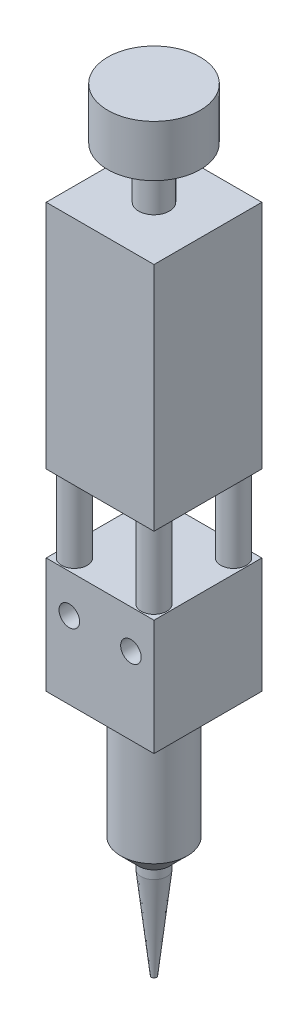
SolidWorks part; units mm, degrees
material "3.1355 (EN-AW 2024)"
ref_plane "Спереди" through (0, 0, 0) normal (0, 0, 1) x (1, 0, 0)
ref_plane "Сверху" through (0, 0, 0) normal (0, 1, 0) x (1, 0, 0)
ref_plane "Справа" through (0, 0, 0) normal (1, 0, 0) x (0, 0, -1)
sketch "Эскиз1" plane through (0, 0, 0) normal (0, 1, 0) x (1, 0, 0)
  line L1 (-10.5, 10.5) -> (10.5, 10.5)
  line L2 (-10.5, 10.5) -> (-10.5, -10.5)
  line L3 (-10.5, -10.5) -> (10.5, -10.5)
  line L4 (10.5, 10.5) -> (10.5, -10.5)
  line L5 (-10.5, 10.5) -> (10.5, -10.5) construction
  line L6 (-10.5, -10.5) -> (10.5, 10.5) construction
  point P0 (0, 0)
  dimension "D1" = 21
extrude "База" add sketch "Эскиз1" along normal blind 22.5
sketch "Эскиз2" plane through (0, 0, 0) normal (0, 0, 1) x (1, 0, 0)
  line L0 (0, 0) -> (6.5, 0)
  line L1 (-10.5, 0) -> (10.5, 0) construction
  line L2 (6.5, 0) -> (6.5, -24.5)
  line L3 (6.5, -24.5) -> (3, -28)
  line L4 (3, -28) -> (0, -28)
  line L5 (0, -28) -> (0, 0)
  dimension "D1" = 28
  dimension "D2" = 3
  dimension "D3" = 6.5
  dimension "D4" = 45
revolve "Повернуть1" add sketch "Эскиз2" angle 360 about L5
hole_wizard "Диаметр отверстия Ø4.0 (4)1" positions "Эскиз3" profile "Эскиз4" hole size "Ø4.0" standard "DIN" end condition through all
sketch "Эскиз3" plane through (0, 0, 10.5) normal (0, 0, 1) x (1, 0, 0)
  line L0 (6, 15) -> (0, 15) construction
  line L1 (0, 15) -> (-6, 15) construction
  point P0 (-6, 15)
  point P2 (6, 15)
  dimension "D1" = 12
  dimension "D2" = 15
sketch "Эскиз4" plane through (-6, 15, 10.5) normal (1, 0, 0) x (0, -1, 0)
  line L0 (0, 0) -> (0, 21)
  line L1 (0, 21) -> (2, 21)
  line L2 (2, 21) -> (2, 0)
  line L5 (2, 0) -> (0, 0)
  line L11 (0, -6.35) -> (0, 107.95) construction
  dimension "Диаметр сквозного отверстия" = 4
  dimension "Глубина сквозного отверстия" = 21
sketch "Эскиз8" plane through (0, 0, 0) normal (0, 0, 1) x (1, 0, 0)
  line L0 (0.25, -28) -> (2.5, -28)
  line L1 (0.25, -28) -> (0.25, -48)
  line L2 (2.5, -28) -> (2.5, -30)
  line L5 (0.25, -48) -> (0.5, -48)
  line L6 (0.5, -48) -> (2.5, -30)
  line L7 (-3, -28) -> (3, -28) construction
  line L8 (0, -28) -> (0, -48) construction
  dimension "D1" = 20
  dimension "D2" = 2
  dimension "D3" = 2.25
  dimension "D4" = 0.25
  dimension "D5" = 0.5
revolve "Повернуть4" add sketch "Эскиз8" angle 360 about L8
sketch "Эскиз9" plane through (0, 22.5, 0) normal (0, 1, 0) x (1, 0, 0)
  line L0 (-7.75, 7.75) -> (-7.75, 10.5) construction
  line L1 (10.5, 10.5) -> (-10.5, 10.5) construction
  line L2 (-7.75, 7.75) -> (-10.5, 7.75) construction
  line L3 (-10.5, 10.5) -> (-10.5, -10.5) construction
  line L4 (7.75, 7.75) -> (10.5, 7.75) construction
  line L5 (10.5, -10.5) -> (10.5, 10.5) construction
  line L6 (7.75, -7.75) -> (7.75, -10.5) construction
  line L7 (-10.5, -10.5) -> (10.5, -10.5) construction
  circle A0 centre (-7.75, 7.75) radius 2.5
  circle A1 centre (7.75, 7.75) radius 2.5
  circle A2 centre (7.75, -7.75) radius 2.5
  circle A3 centre (-7.75, -7.75) radius 2.5
  dimension "D1" = 5
  dimension "D2" = 2.75
extrude "Бобышка-Вытянуть1" add sketch "Эскиз9" along normal blind 15
sketch "Эскиз10" plane through (0, 37.5, 0) normal (0, 1, 0) x (1, 0, 0)
  line L1 (-10.5, 10.5) -> (10.5, 10.5)
  line L2 (-10.5, 10.5) -> (-10.5, -10.5)
  line L3 (-10.5, -10.5) -> (10.5, -10.5)
  line L4 (10.5, 10.5) -> (10.5, -10.5)
extrude "Бобышка-Вытянуть2" add sketch "Эскиз10" along normal blind 45
sketch "Эскиз7" plane through (0, 0, 0) normal (0, 0, 1) x (1, 0, 0)
  line L0 (0, 82.5) -> (0, 102.5)
  line L2 (0, 102.5) -> (9, 102.5)
  line L3 (9, 102.5) -> (9, 92.5)
  line L4 (9, 92.5) -> (3, 92.5)
  line L5 (3, 92.5) -> (3, 82.5)
  line L6 (3, 82.5) -> (0, 82.5)
  line L7 (-10.5, 82.5) -> (10.5, 82.5) construction
  dimension "D1" = 20
  dimension "D2" = 9
  dimension "D3" = 10
  dimension "D4" = 3
revolve "Повернуть3" add sketch "Эскиз7" angle 360 about L0
